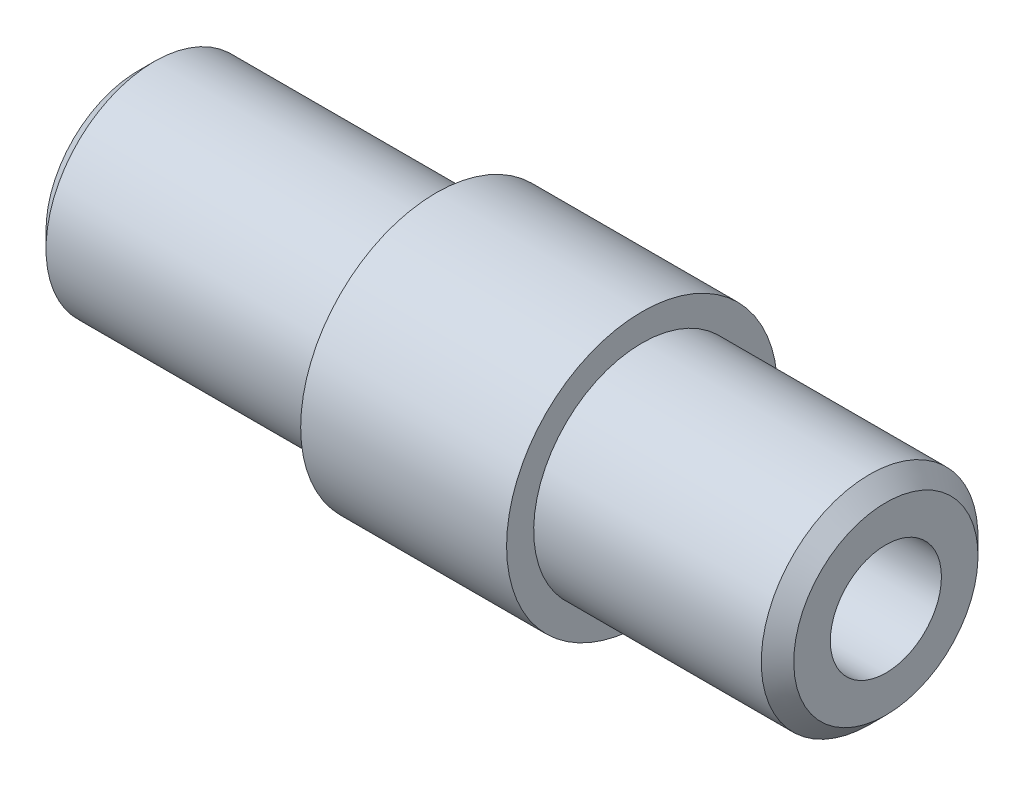
SolidWorks part; units mm, degrees
material "Acier allié inoxydable"
ref_plane "Face" through (0, 0, 0) normal (0, 0, 1) x (1, 0, 0)
ref_plane "Dessus" through (0, 0, 0) normal (0, 1, 0) x (1, 0, 0)
ref_plane "Droite" through (0, 0, 0) normal (1, 0, 0) x (0, 0, -1)
sketch "Esquisse1" plane through (0, 0, 0) normal (0, 0, 1) x (1, 0, 0)
  line L0 (0, 0) -> (0, 2)
  line L1 (0, 2) -> (5.5, 2)
  line L2 (5.5, 2) -> (5.5, 2.5)
  line L4 (13.8, 0) -> (13.8, 2)
  line L5 (5.5, 2.5) -> (9.3, 2.5)
  line L6 (9.3, 2.5) -> (9.3, 2)
  line L7 (13.8, 0) -> (0, 0) construction
  line L8 (0, 0) -> (13.8, 0)
  line L9 (13.8, 2) -> (9.3, 2)
  dimension "D1" = 4
  dimension "D2" = 5.5
  dimension "D3" = 4.5
  dimension "D5" = 3.8
  dimension "D6" = 5
revolve "Révolution1" add sketch "Esquisse1" angle 360 about L7
hole_wizard "Trou taraudé M2.52" positions "Esquisse6" profile "Esquisse5" tap size "M2.5" standard "Iso"
sketch "Esquisse6" plane through (0, 0, 0) normal (-1, 0, 0) x (0, 0, 1)
  point P0 (0, 0)
cosmetic thread "Filetage de perçage4" parameters "D1"=6, "D2"=2.5
sketch "Esquisse5" plane through (0, 0, 0) normal (0, 1, 0) x (0, 0, 1)
  line L0 (0, 0) -> (0, 7.9659)
  line L1 (0, 7.9659) -> (1.025, 7.35)
  line L2 (1.025, 7.35) -> (1.025, 0)
  line L5 (1.025, 0) -> (0, 0)
  line L10 (0, 7.9659) -> (-1.025, 7.35) construction
  line L11 (0, -6.35) -> (0, 107.95) construction
  dimension "Diamètre du trou pour taraudage" = 2.05
  dimension "Profondeur du trou pour taraudage" = 7.35
  dimension "Angle de pointe" = 118
hole_wizard "Trou taraudé M2.51" positions "Esquisse8" profile "Esquisse7" tap size "M2.5" standard "Iso" end condition through all
sketch "Esquisse8" plane through (13.8, 0, 0) normal (1, 0, 0) x (0, 0, -1)
  point P0 (0, 0)
cosmetic thread "Filetage de perçage5" parameters "D1"=6, "D2"=2.5
sketch "Esquisse7" plane through (13.8, 0, 0) normal (0, 1, 0) x (0, 0, -1)
  line L0 (0, 0) -> (0, 13.8)
  line L1 (0, 13.8) -> (1.025, 13.8)
  line L2 (1.025, 13.8) -> (1.025, 0)
  line L5 (1.025, 0) -> (0, 0)
  line L11 (0, -6.35) -> (0, 107.95) construction
  dimension "Diamètre du trou pour taraudage jusqu'au prochain" = 2.05
  dimension "Profondeur du trou pour taraudage jusqu'au prochain" = 13.8
chamfer "Chanfrein1" distance 0.3 angle 45 2 edges at (13.8, 2, 0) (0, 2, 0)
